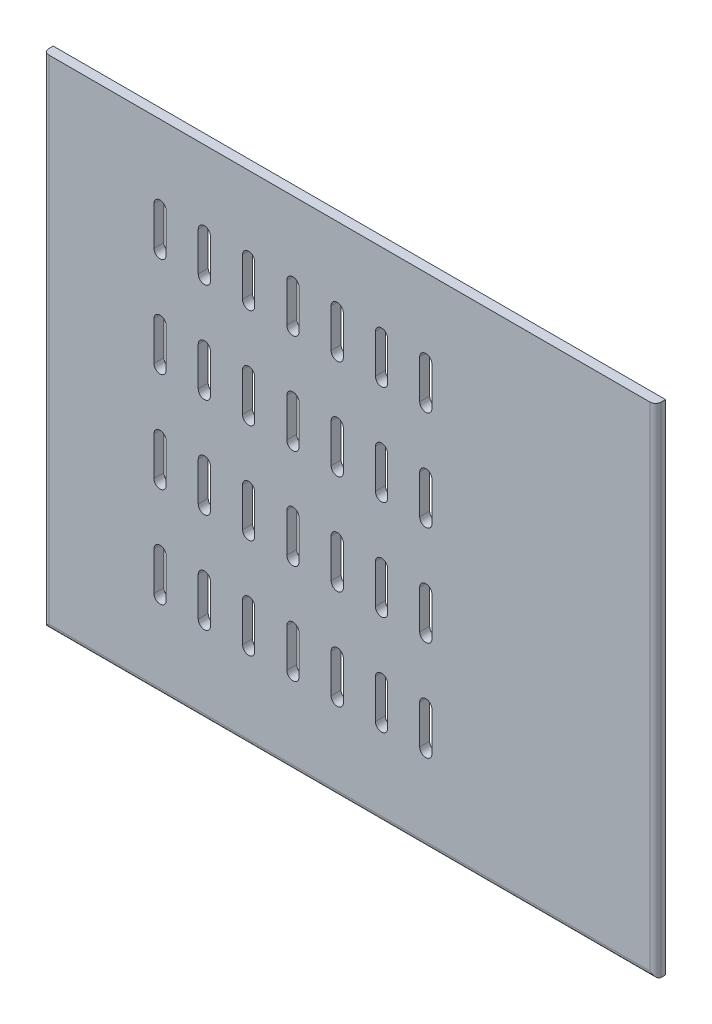
SolidWorks part; units mm, degrees
ref_plane "Front Plane" through (0, 0, 0) normal (0, 0, 1) x (1, 0, 0)
ref_plane "Top Plane" through (0, 0, 0) normal (0, 1, 0) x (1, 0, 0)
ref_plane "Right Plane" through (0, 0, 0) normal (1, 0, 0) x (0, 0, -1)
sketch "Sketch for the main shape" plane through (0, 0, 0) normal (0, 0, 1) x (1, 0, 0)
  line L1 (0, 0) -> (110.6, 0)
  line L2 (0, 0) -> (0, 90)
  line L3 (0, 90) -> (110.6, 90)
  line L4 (110.6, 0) -> (110.6, 90)
  dimension "D1" = 90
  dimension "D2" = 110.6
extrude "Main Shape" add sketch "Sketch for the main shape" along normal blind 1.8
sketch "Sketch for the railings" plane through (0, 0, 0) normal (1, 0, 0) x (0, 0, -1)
  line L0 (0, 10.9) -> (3, 10.9)
  line L1 (0, 0) -> (0, 90) construction
  line L2 (3, 10.9) -> (0, 8.2542)
  line L3 (0, 8.2542) -> (0, 10.9)
  dimension "D1" = 3
  dimension "D2" = 4
  dimension "D3" = 10.9
extrude "Railings for the PCB" add sketch "Sketch for the railings" along normal blind 80
pattern_linear "Pattern the the railings" count 4 spacing 18 along (0, 1, 0) of "Railings for the PCB"
sketch "Sketch for the air vents" plane through (0, 0, 0) normal (0, 0, -1) x (-1, 0, 0)
  line L0 (-21.1013, 22.2542) -> (-21.1013, 15.2542) construction
  line L1 (-20, 22.2542) -> (-20, 15.2542)
  line L2 (-22.2025, 22.2542) -> (-22.2025, 15.2542)
  line L3 (-80, 26.2542) -> (0, 26.2542) construction
  line L4 (0, 26.2542) -> (0, 10.9) construction
  arc A0 (-20, 22.2542) -> (-22.2025, 22.2542) centre (-21.1013, 22.2542) ccw
  arc A1 (-22.2025, 15.2542) -> (-20, 15.2542) centre (-21.1013, 15.2542) ccw
  point P2 (-21.1013, 18.7542)
  dimension "D3" = 1.1013
  dimension "D1" = 7
  dimension "D2" = 4
  dimension "D4" = 20
extrude "Air vents" cut sketch "Sketch for the air vents" against normal blind 1.8
pattern_linear "pattern along x axis for the vent" count 7 spacing 8 along (1, 0, 0) of "Air vents"
pattern_linear "pattern along y axis for the vent" count 4 spacing 18 along (0, 1, 0) of "pattern along x axis for the vent", "Air vents"
sketch "Sketch for the small gap between the edge and the railing" plane through (0, 0, 0) normal (-1, 0, 0) x (0, 0, 1)
  line L0 (0, 8.2542) -> (-3, 10.9)
  line L1 (-3, 10.9) -> (0, 10.9)
  line L2 (0, 10.9) -> (0, 8.2542)
extrude "small gap between the edge and the railing" cut sketch "Sketch for the small gap between the edge and the railing" against normal blind 2
pattern_linear "pattern for th small gap" count 4 spacing 18 along (0, 1, 0) of "small gap between the edge and the railing"
fillet "Fillets" radius 1 3 edges at (110.6, 45, 1.8) (55.3, 0, 1.8) (0, 45, 1.8)
